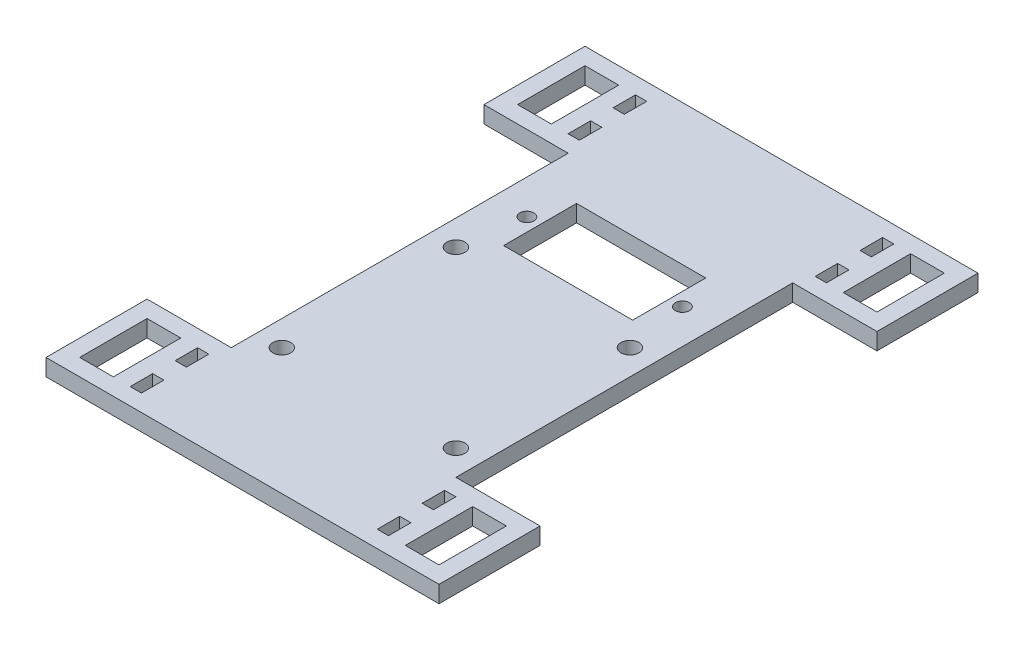
SolidWorks part; units mm, degrees
ref_plane "前视基准面" through (0, 0, 0) normal (0, 0, 1) x (1, 0, 0)
ref_plane "上视基准面" through (0, 0, 0) normal (0, 1, 0) x (1, 0, 0)
ref_plane "右视基准面" through (0, 0, 0) normal (1, 0, 0) x (0, 0, -1)
sketch "草图1" plane through (0, 0, 0) normal (0, 1, 0) x (1, 0, 0)
  line L0 (20, -20) -> (35, -20)
  line L2 (-20, 20) -> (-20, -20)
  line L4 (20, 20) -> (20, -20)
  line L5 (-20, 20) -> (20, -20) construction
  line L6 (-20, -20) -> (20, 20) construction
  line L8 (-20, 40) -> (-20, 20)
  line L10 (20, 40) -> (20, 20)
  line L11 (-20, 40) -> (20, 20) construction
  line L12 (-20, 20) -> (20, 40) construction
  line L13 (-35, -20) -> (-20, -20)
  line L14 (-35, -20) -> (-35, -38)
  line L15 (-35, -38) -> (35, -38)
  line L16 (35, -20) -> (35, -38)
  line L17 (-35, -20) -> (35, -38) construction
  line L18 (-35, -38) -> (35, -20) construction
  line L19 (20, 40) -> (35, 40)
  line L20 (-35, 58) -> (35, 58)
  line L21 (-35, 58) -> (-35, 40)
  line L22 (-35, 40) -> (-20, 40)
  line L23 (35, 58) -> (35, 40)
  line L24 (-35, 58) -> (35, 40) construction
  line L25 (-35, 40) -> (35, 58) construction
  point P0 (0, 0)
  point P2 (0, -29)
  point P6 (0, 30)
  point P15 (0, 49)
  dimension "D1" = 40
  dimension "D2" = 40
  dimension "D3" = 20
  dimension "D4" = 18
  dimension "D5" = 70
  dimension "D6" = 18
  dimension "D7" = 70
extrude "凸台-拉伸1" add sketch "草图1" along normal blind 3
sketch "草图2" plane through (0, 3, 0) normal (0, 1, 0) x (1, 0, 0)
  line L0 (-1000, 0) -> (49000, 0) construction
  line L1 (0, -1000) -> (0, 49000) construction
  line L2 (-1035, -29) -> (48965, -29) construction
  line L7 (35, -20) -> (20, -20) construction
  line L8 (-11.5, 33) -> (11.5, 33)
  line L9 (-35, -20) -> (-35, -38) construction
  line L10 (-11.5, 33) -> (-11.5, 20)
  line L11 (-23, -31) -> (-21, -31)
  line L12 (-11.5, 20) -> (11.5, 20)
  line L13 (11.5, 33) -> (11.5, 20)
  line L14 (-11.5, 33) -> (11.5, 20) construction
  line L15 (-11.5, 20) -> (11.5, 33) construction
  line L16 (-1000, 26.5) -> (49000, 26.5) construction
  line L17 (-32, -23) -> (-26, -23)
  line L18 (-32, -23) -> (-32, -35)
  line L19 (-32, -35) -> (-26, -35)
  line L20 (-26, -23) -> (-26, -35)
  line L21 (-32, -23) -> (-26, -35) construction
  line L22 (-32, -35) -> (-26, -23) construction
  line L23 (-23, -23) -> (-21, -23)
  line L24 (-23, -23) -> (-23, -27)
  line L25 (-23, -27) -> (-21, -27)
  line L26 (-21, -23) -> (-21, -27)
  line L27 (-23, -23) -> (-21, -27) construction
  line L28 (-23, -27) -> (-21, -23) construction
  line L29 (-21, -35) -> (-21, -31)
  line L30 (-23, -35) -> (-21, -35)
  line L31 (-23, -35) -> (-23, -31)
  line L32 (23, -35) -> (23, -31)
  line L33 (23, -35) -> (21, -35)
  line L34 (21, -35) -> (21, -31)
  line L35 (23, -31) -> (21, -31)
  line L36 (23, -27) -> (21, -27)
  line L37 (21, -23) -> (21, -27)
  line L38 (23, -23) -> (21, -23)
  line L39 (23, -23) -> (23, -27)
  line L40 (32, -35) -> (26, -35)
  line L41 (26, -23) -> (26, -35)
  line L42 (32, -23) -> (26, -23)
  line L43 (32, -23) -> (32, -35)
  line L44 (-1035, 49) -> (48965, 49) construction
  line L45 (-35, 58) -> (-35, 40) construction
  line L46 (-23, 47) -> (-21, 47)
  line L47 (-32, 43) -> (-26, 43)
  line L48 (-32, 43) -> (-32, 55)
  line L49 (-32, 55) -> (-26, 55)
  line L50 (-26, 43) -> (-26, 55)
  line L51 (-32, 43) -> (-26, 55) construction
  line L52 (-32, 55) -> (-26, 43) construction
  line L53 (-23, 55) -> (-21, 55)
  line L54 (-23, 55) -> (-23, 51)
  line L55 (-23, 51) -> (-21, 51)
  line L56 (-21, 55) -> (-21, 51)
  line L57 (-23, 55) -> (-21, 51) construction
  line L58 (-23, 51) -> (-21, 55) construction
  line L59 (-21, 43) -> (-21, 47)
  line L60 (-23, 43) -> (-21, 43)
  line L61 (-23, 43) -> (-23, 47)
  line L62 (23, 43) -> (21, 43)
  line L63 (23, 43) -> (23, 47)
  line L64 (21, 43) -> (21, 47)
  line L65 (23, 47) -> (21, 47)
  line L66 (23, 51) -> (21, 51)
  line L67 (21, 55) -> (21, 51)
  line L68 (23, 55) -> (21, 55)
  line L69 (23, 55) -> (23, 51)
  line L70 (32, 43) -> (26, 43)
  line L71 (26, 43) -> (26, 55)
  line L72 (32, 43) -> (32, 55)
  line L73 (32, 55) -> (26, 55)
  circle A0 centre (-15.5, -15.5) radius 1.6
  circle A1 centre (-15.5, 15.5) radius 1.6
  circle A2 centre (15.5, -15.5) radius 1.6
  circle A3 centre (15.5, 15.5) radius 1.6
  circle A6 centre (-13.85, 26.5) radius 1.25
  circle A7 centre (13.85, 26.5) radius 1.25
  point P13 (0, 26.5)
  point P27 (-29, -29)
  point P31 (-35, -29)
  point P36 (-22, -25)
  point P58 (-29, 49)
  point P62 (-35, 49)
  point P67 (-22, 53)
  dimension "D1" = 3.2
  dimension "D7" = 2.5
  dimension "D2" = 31
  dimension "D3" = 31
  dimension "D4" = 23
  dimension "D5" = 13
  dimension "D6" = 40
  dimension "D8" = 27.7
  dimension "D9" = 12
  dimension "D10" = 6
  dimension "D11" = 3
  dimension "D12" = 2
  dimension "D13" = 4
  dimension "D14" = 3
  dimension "D15" = 12
  dimension "D16" = 6
  dimension "D17" = 3
  dimension "D18" = 4
  dimension "D19" = 2
  dimension "D20" = 3
extrude "切除-拉伸1" cut sketch "草图2" against normal up to next
